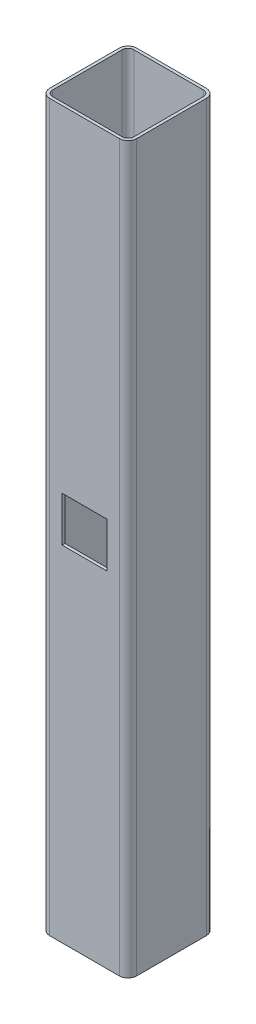
SolidWorks part; units mm, degrees
material "Plain Carbon Steel"
ref_plane "Front Plane" through (0, 0, 0) normal (0, 0, 1) x (1, 0, 0)
ref_plane "Top Plane" through (0, 0, 0) normal (0, 1, 0) x (1, 0, 0)
ref_plane "Right Plane" through (0, 0, 0) normal (1, 0, 0) x (0, 0, -1)
sketch "Sketch1" plane through (0, 0, 0) normal (0, 1, 0) x (1, 0, 0)
  line L1 (-24, -30) -> (24, -30)
  line L2 (-30, -24) -> (-30, 24)
  line L3 (-24, 30) -> (24, 30)
  line L4 (30, -24) -> (30, 24)
  line L5 (-30, -30) -> (30, 30) construction
  line L6 (-30, 30) -> (30, -30) construction
  arc A0 (30, -24) -> (24, -30) centre (24, -24) cw
  arc A1 (30, 24) -> (24, 30) centre (24, 24) ccw
  arc A2 (-24, 30) -> (-30, 24) centre (-24, 24) ccw
  arc A3 (-24, -30) -> (-30, -24) centre (-24, -24) cw
  point P0 (0, 0)
  dimension "D3" = 6
  dimension "D1" = 60
  dimension "D2" = 60
extrude "Boss-Extrude1" add sketch "Sketch1" along normal mid plane 500
shell "Shell1" thickness 2
sketch "Sketch2" plane through (0, 0, -30) normal (0, 0, -1) x (-1, 0, 0)
  line L1 (-15.5, 18.5021) -> (15.5, 18.5021)
  line L2 (-15.5, 18.5021) -> (-15.5, -12.4979)
  line L3 (-15.5, -12.4979) -> (15.5, -12.4979)
  line L4 (15.5, 18.5021) -> (15.5, -12.4979)
  line L5 (-15.5, 18.5021) -> (15.5, -12.4979) construction
  line L6 (-15.5, -12.4979) -> (15.5, 18.5021) construction
  line L7 (0, 33) -> (0, -33) construction
  line L9 (-27.4108, 3.0021) -> (27.4108, 3.0021) construction
  point P0 (0, 3.0021)
  dimension "D1" = 31
  dimension "D2" = 31
extrude "Cut-Extrude1" cut sketch "Sketch2" against normal through all
sketch "Sketch3" [suppressed] plane through (0, 0, -30) normal (0, 0, -1) x (-1, 0, 0)
  circle A0 centre (0, 0) radius 17.5
  dimension "D1" = 35
extrude "Cut-Extrude2" [suppressed] cut sketch "Sketch3" against normal through all
sketch "Sketch4" [suppressed] plane through (0, 0, -30) normal (0, 0, -1) x (-1, 0, 0)
  circle A0 centre (0, -270) radius 6 construction
  circle A1 centre (0, -220) radius 6 construction
  circle A2 centre (0, -270) radius 6
  circle A3 centre (0, -220) radius 6
extrude "Cut-Extrude3" [suppressed] cut sketch "Sketch4" against normal through all
